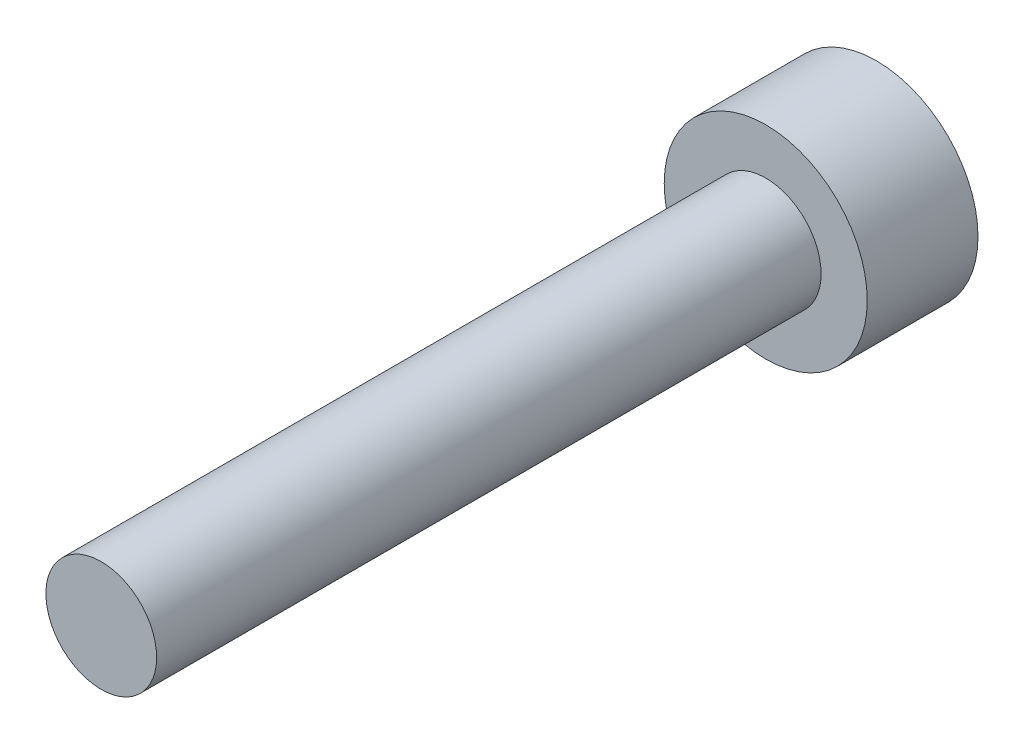
SolidWorks part; units mm, degrees
ref_plane "Front Plane" through (0, 0, 0) normal (0, 0, 1) x (1, 0, 0)
ref_plane "Top Plane" through (0, 0, 0) normal (0, 1, 0) x (1, 0, 0)
ref_plane "Right Plane" through (0, 0, 0) normal (1, 0, 0) x (0, 0, -1)
sketch "S01 - Head" plane through (0, 0, 0) normal (0, 0, 1) x (1, 0, 0)
  circle A0 centre (0, 0) radius 2.75
  dimension "D1" = 5.5
extrude "01 - Head" add sketch "S01 - Head" along normal blind 3 from offset 3
sketch "S02 - Nominal shank" plane through (0, 0, 0) normal (0, 0, 1) x (1, 0, 0)
  circle A0 centre (0, 0) radius 1.5
  dimension "D1" = 3
extrude "02 - Nominal shank" add sketch "S02 - Nominal shank" along normal blind 18
sketch "S03 - Hex key socket" plane through (0, 0, 0) normal (0, 0, 1) x (1, 0, 0)
  line L0 (1.4434, 0) -> (0.7217, 1.25)
  line L1 (0.7217, 1.25) -> (-0.7217, 1.25)
  line L2 (-0.7217, 1.25) -> (-1.4434, 0)
  line L3 (-1.4434, 0) -> (-0.7217, -1.25)
  line L4 (-0.7217, -1.25) -> (0.7217, -1.25)
  line L5 (0.7217, -1.25) -> (1.4434, 0)
  dimension "D1" = 0.7217
  dimension "D2" = 1.4434
  dimension "D3" = 0.7217
  dimension "D4" = 1.4434
  dimension "D5" = 1.25
  dimension "D6" = 1.25
extrude "03 - Hex key socket" cut sketch "S03 - Hex key socket" along normal blind 1.75 from offset 3.1
